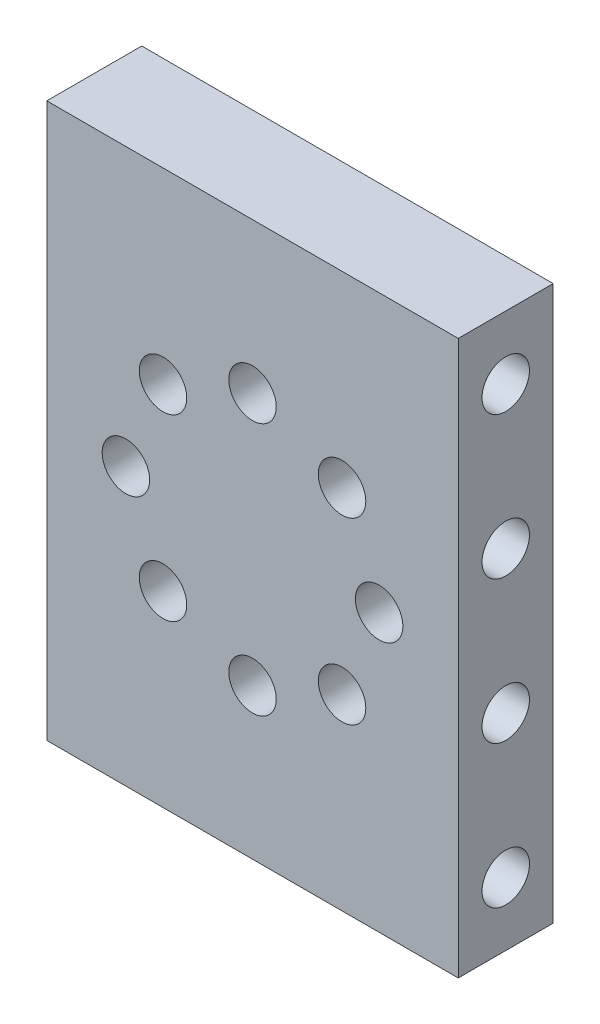
SolidWorks part; units mm, degrees
ref_plane "前视基准面" through (0, 0, 0) normal (0, 0, 1) x (1, 0, 0)
ref_plane "上视基准面" through (0, 0, 0) normal (0, 1, 0) x (1, 0, 0)
ref_plane "右视基准面" through (0, 0, 0) normal (1, 0, 0) x (0, 0, -1)
sketch "草图1" plane through (0, 0, 0) normal (0, 0, 1) x (1, 0, 0)
  line L1 (26, -35) -> (-26, -35)
  line L2 (26, -35) -> (26, 35)
  line L3 (26, 35) -> (-26, 35)
  line L4 (-26, -35) -> (-26, 35)
  line L5 (26, -35) -> (-26, 35) construction
  line L6 (26, 35) -> (-26, -35) construction
  point P0 (0, 0)
  dimension "D1" = 52
  dimension "D2" = 70
extrude "凸台-拉伸1" add sketch "草图1" along normal blind 12
sketch "草图2" plane through (-26, 0, 0) normal (-1, 0, 0) x (0, 0, 1)
  line L0 (12, 35) -> (0, 35) construction
  circle A0 centre (6, 27) radius 3
  circle A1 centre (6, 9) radius 3
  circle A2 centre (6, -9) radius 3
  circle A3 centre (6, -27) radius 3
  dimension "D1" = 6
  dimension "D2" = 8
  dimension "D3" = 4
extrude "切除-拉伸1" cut sketch "草图2" against normal blind 10
sketch "草图3" plane through (26, 0, 0) normal (1, 0, 0) x (0, 0, -1)
  line L0 (-12, 35) -> (0, 35) construction
  circle A0 centre (-6, 27) radius 3
  circle A1 centre (-6, 9) radius 3
  circle A2 centre (-6, -9) radius 3
  circle A3 centre (-6, -27) radius 3
  dimension "D1" = 6
  dimension "D2" = 8
  dimension "D3" = 4
extrude "切除-拉伸2" cut sketch "草图3" against normal blind 10
sketch "草图4" plane through (0, 0, 12) normal (0, 0, 1) x (1, 0, 0)
  circle A0 centre (0, 0) radius 16 construction
  circle A1 centre (16, 0) radius 3
  circle A2 centre (11.3137, -11.3137) radius 3
  circle A3 centre (0, -16) radius 3
  circle A4 centre (-11.3137, -11.3137) radius 3
  circle A5 centre (-16, 0) radius 3
  circle A6 centre (-11.3137, 11.3137) radius 3
  circle A7 centre (0, 16) radius 3
  circle A8 centre (11.3137, 11.3137) radius 3
  dimension "D1" = 32
  dimension "D2" = 6
  dimension "D3" = 8
extrude "切除-拉伸3" cut sketch "草图4" against normal blind 12
